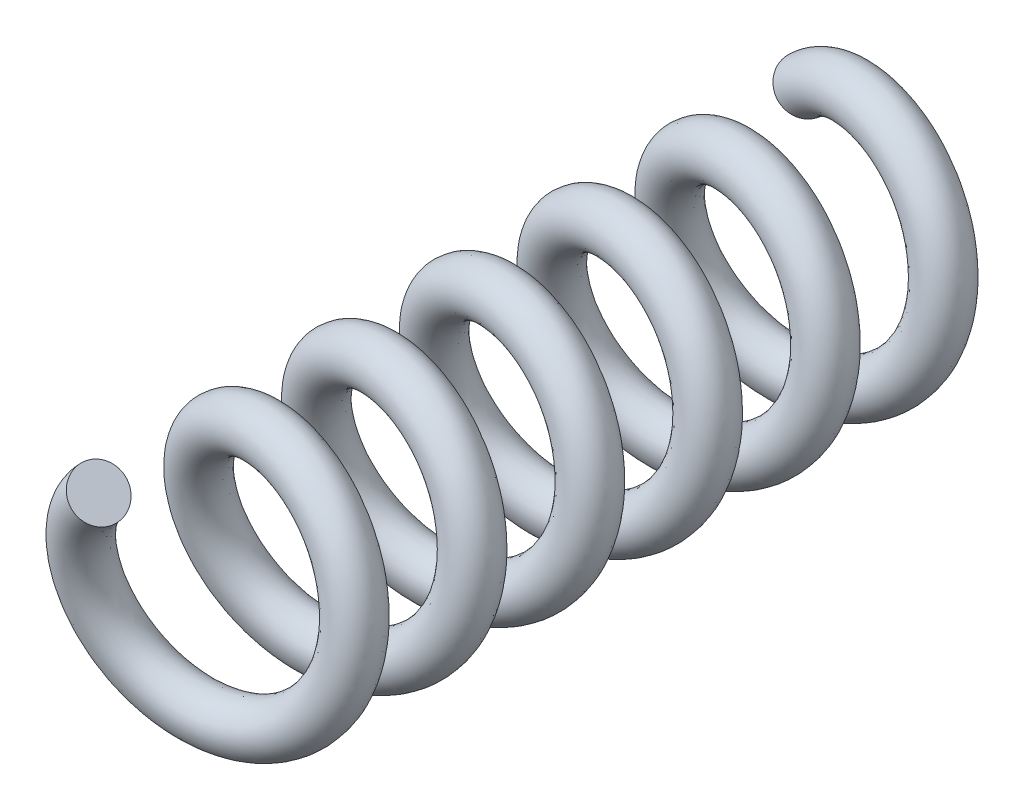
SolidWorks part; units mm, degrees
ref_plane "Piano frontale" through (0, 0, 0) normal (0, 0, 1) x (1, 0, 0)
ref_plane "Piano superiore" through (0, 0, 0) normal (0, 1, 0) x (1, 0, 0)
ref_plane "Piano destro" through (0, 0, 0) normal (1, 0, 0) x (0, 0, -1)
sketch "Schizzo1" plane through (0, 0, 0) normal (0, 0, 1) x (1, 0, 0)
  circle A0 centre (0, 0) radius 15
  dimension "D1" = 30
curve "Elica/Spirale1" pitch 16.7217 height 100.33 turns 6
sweep "Sweep1" add path "Elica/Spirale1" circular profile diameter 7 parameters "D3"=7
